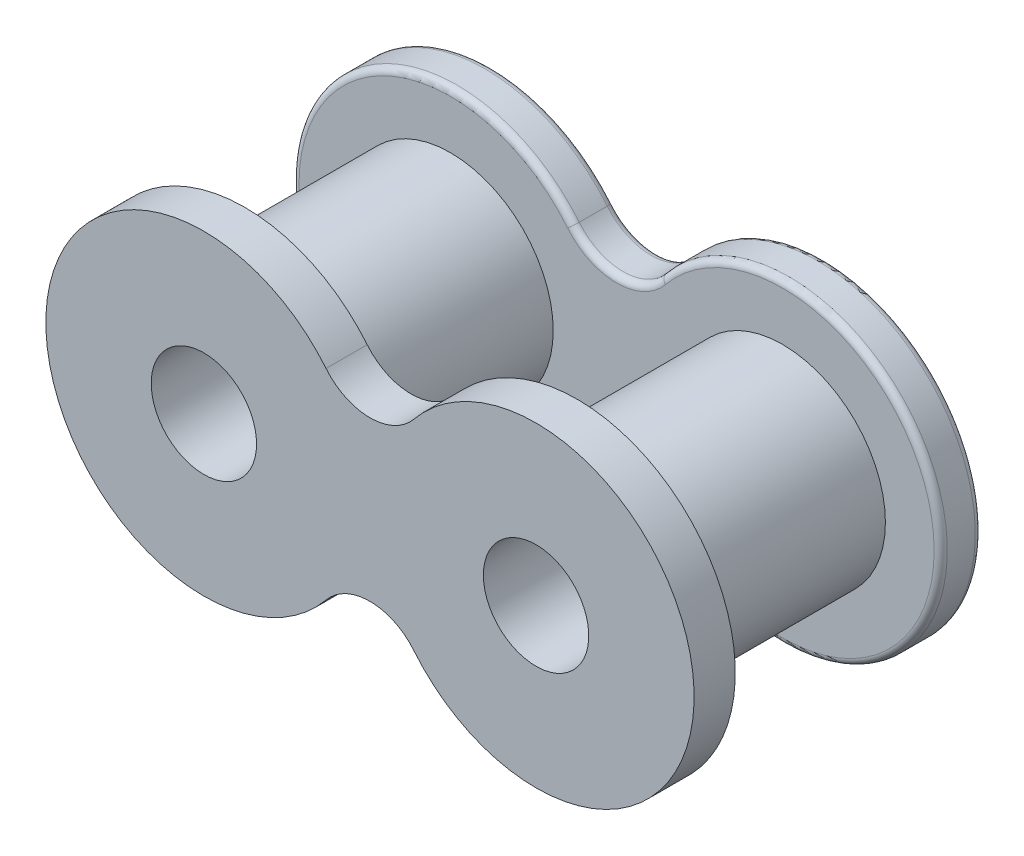
SolidWorks part; units mm, degrees
material "AISI 304"
ref_plane "Front Plane" through (0, 0, 0) normal (0, 0, 1) x (1, 0, 0)
ref_plane "Top Plane" through (0, 0, 0) normal (0, 1, 0) x (1, 0, 0)
ref_plane "Right Plane" through (0, 0, 0) normal (1, 0, 0) x (0, 0, -1)
sketch "Sketch1" plane through (0, 0, 0) normal (0, 0, 1) x (1, 0, 0)
  line L0 (0, 7.1722) -> (0, 3.0657) construction
  line L1 (-9.7016, 0) -> (11.7112, 0) construction
  line L2 (0, -3.0657) -> (0, -8.4889) construction
  circle A0 centre (-6.4064, 0) radius 2.032
  arc A1 (-1.6939, 3.867) -> (-1.6939, -3.867) centre (-6.4064, 0) ccw
  circle A2 centre (6.4064, 0) radius 2.032
  arc A3 (1.6939, 3.867) -> (1.6939, -3.867) centre (6.4064, 0) cw
  arc A4 (-1.6939, 3.867) -> (1.6939, 3.867) centre (0, 5.2569) ccw
  arc A5 (-1.6939, -3.867) -> (1.6939, -3.867) centre (0, -5.2569) cw
  dimension "D1" = 4.064
  dimension "D2" = 12.192
  dimension "D3" = 6.4064
extrude "Boss-Extrude1" add sketch "Sketch1" along normal blind 1.5875
fillet "Fillet1" radius 0.254 12 edges at (4.3744, 0, 0) (-4.3744, 0, 0) (-12.5024, 0, 0) (0, -3.0657, 0) (12.5024, 0, 0) (0, 3.0657, 0) (4.3744, 0, 1.5875) (12.5024, 0, 1.5875) (0, -3.0657, 1.5875) (-12.5024, 0, 1.5875) (0, 3.0657, 1.5875) (-4.3744, 0, 1.5875)
sketch "Sketch2" plane through (0, 0, 1.5875) normal (0, 0, 1) x (1, 0, 0)
  circle A0 centre (-6.4064, 0) radius 2.032 construction
  circle A1 centre (-6.4064, 0) radius 2.032
  circle A2 centre (-6.4064, 0) radius 3.9624
  dimension "D1" = 7.9248
extrude "Boss-Extrude2" add sketch "Sketch2" along normal blind 7.9248
mirror "Mirror1" about plane through (0, 0, 0) normal (1, 0, 0) of "Boss-Extrude2"
ref_plane "Plane1" through (0, 0, 5.5499) normal (0, 0, 1) x (1, 0, 0)
mirror "Mirror2" about plane through (0, 0, 5.5499) normal (0, 0, 1) of "Boss-Extrude1"
